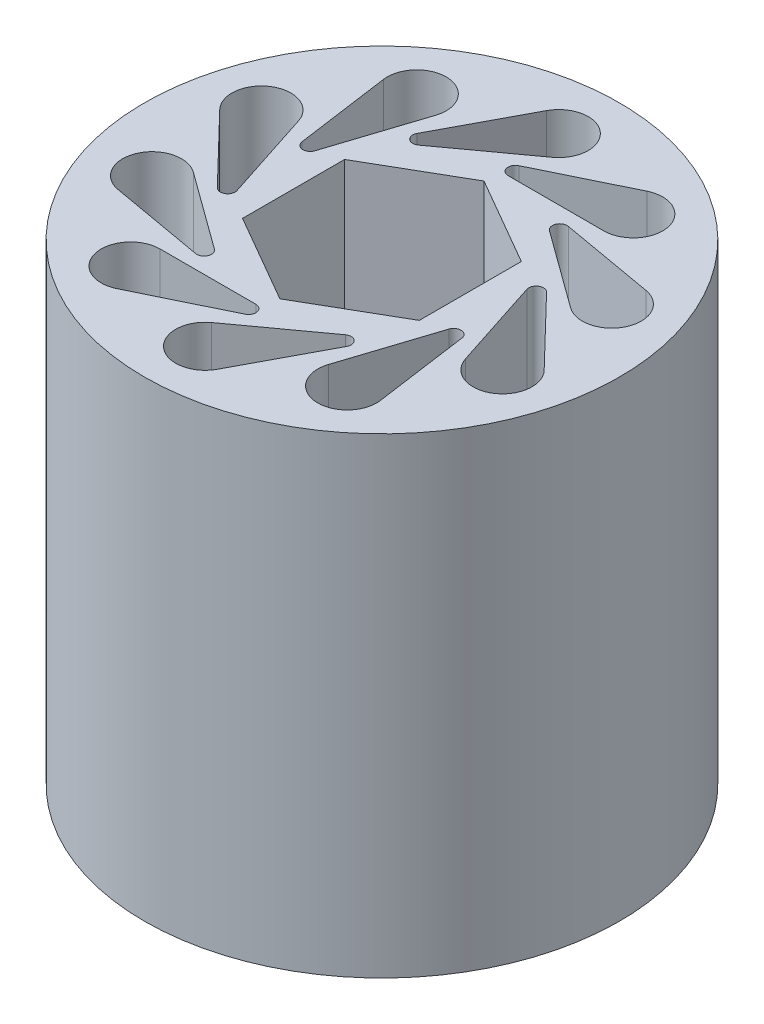
SolidWorks part; units mm, degrees
ref_plane "Front Plane" through (0, 0, 0) normal (0, 0, 1) x (1, 0, 0)
ref_plane "Top Plane" through (0, 0, 0) normal (0, 1, 0) x (1, 0, 0)
ref_plane "Right Plane" through (0, 0, 0) normal (1, 0, 0) x (0, 0, -1)
sketch "Sketch1" plane through (0, 0, 0) normal (0, 1, 0) x (1, 0, 0)
  line L0 (0, 0) -> (0, 25.6) construction
  line L1 (0, 12.8) -> (22.1703, 12.8) construction
  line L2 (0, 14.0898) -> (17.5057, 22.6239) construction
  line L3 (0.7937, 13.5938) -> (11.1125, 15.975) construction
  line L4 (0, 12.8) -> (19.7727, 12.8) construction
  line L5 (0.4459, 14.3072) -> (9.7212, 18.8289)
  line L6 (0.7937, 12.8) -> (11.1125, 12.8)
  line L7 (8.2915, 6.1775) -> (8.332, 6.1636)
  line L8 (8.7703, 11.3127) -> (18.932, 9.5189)
  line L9 (8.1658, 9.8889) -> (16.5139, 3.8237)
  line L10 (13.7448, 3.9971) -> (20.9114, -3.427)
  line L11 (12.4188, 3.2005) -> (15.6075, -6.6132)
  line L12 (13.4692, -4.8453) -> (14.9034, -15.0639)
  line L13 (11.9282, -4.7103) -> (8.7396, -14.524)
  line L14 (8.0488, -11.8369) -> (3.2027, -20.9469)
  line L15 (6.8815, -10.822) -> (-1.4666, -16.8872)
  line L16 (-0.4459, -14.3072) -> (-9.7212, -18.8289)
  line L17 (-0.7937, -12.8) -> (-11.1125, -12.8)
  line L18 (-8.7703, -11.3127) -> (-18.932, -9.5189)
  line L19 (-8.1658, -9.8889) -> (-16.5139, -3.8237)
  line L20 (0, 21.4691) -> (3.3271, 24.7962)
  line L21 (-12.8, 12.29) -> (-12.8, 22.6088) [skipped]
  line L22 (-20.4454, 24.5333) -> (-20.8126, 25.2866) [skipped]
  line L23 (-16.1802, 4.0758) -> (-25.9361, 7.4371) [skipped]
  line L24 (-15.3604, 5.3875) -> (-22.6568, 12.684) [skipped]
  line L25 (-11.9422, -2.811) -> (-21.2175, -7.3327) [skipped]
  line L26 (-12.29, -1.3037) -> (-22.6088, -1.3037) [skipped]
  line L27 (-11.0512, -9.5278) -> (-15.2391, -13.7157) [skipped]
  line L28 (-6.8663, -12.7832) -> (-8.9617, -18.865) [skipped]
  line L29 (1.3037, -13.3766) -> (1.3037, -14.1925) [skipped]
  line L30 (4.483, -3.8758) -> (7.6655, -10.4039) [skipped]
  line L31 (11.4871, -1.5143) -> (13.4593, -3.4864) [skipped]
  line L32 (-7.4205, 16.1802) -> (-4.0592, 25.9361) [skipped]
  line L33 (-13.7448, -3.9971) -> (-20.9114, 3.427)
  line L34 (-12.4188, -3.2005) -> (-15.6075, 6.6132)
  line L35 (-13.4692, 4.8453) -> (-14.9034, 15.0639)
  line L36 (-11.9282, 4.7103) -> (-8.7396, 14.524)
  line L37 (-8.0488, 11.8369) -> (-3.2027, 20.9469)
  line L38 (-6.8815, 10.822) -> (1.4666, 16.8872)
  line L40 (0, 10.9985) -> (-9.525, 5.4993)
  line L41 (-9.525, 5.4993) -> (-9.525, -5.4993)
  line L42 (-9.525, -5.4993) -> (0, -10.9985)
  line L43 (0, -10.9985) -> (9.525, -5.4993)
  line L44 (9.525, -5.4993) -> (9.525, 5.4993)
  line L45 (9.525, 5.4993) -> (0, 10.9985)
  circle A0 centre (0, 0) radius 25.6
  circle A1 centre (0, 0) radius 10.364 construction
  circle A2 centre (11.1125, 15.975) radius 3.175 construction
  circle A3 centre (0.7937, 13.5938) radius 0.7937 construction
  arc A4 (0.4459, 14.3072) -> (0.7937, 12.8) centre (0.7937, 13.5938) ccw
  arc A5 (11.1125, 12.8) -> (9.7212, 18.8289) centre (11.1125, 15.975) ccw
  arc A6 (1.5672, 13.7722) -> (1.5528, 13.8258) centre (0.7937, 13.5938) ccw
  arc A7 (16.5139, 3.8237) -> (18.932, 9.5189) centre (18.3801, 6.3923) ccw
  arc A8 (8.7703, 11.3127) -> (8.1658, 9.8889) centre (8.6324, 10.531) ccw
  arc A9 (15.6075, -6.6132) -> (20.9114, -3.427) centre (18.6271, -5.6321) ccw
  arc A10 (13.7448, 3.9971) -> (12.4188, 3.2005) centre (13.1737, 3.4458) ccw
  arc A11 (8.7396, -14.524) -> (14.9034, -15.0639) centre (11.7592, -15.5052) ccw
  arc A12 (13.4692, -4.8453) -> (11.9282, -4.7103) centre (12.6831, -4.9556) ccw
  arc A13 (-1.4666, -16.8872) -> (3.2027, -20.9469) centre (0.3997, -19.4558) ccw
  arc A14 (8.0488, -11.8369) -> (6.8815, -10.822) centre (7.348, -11.4641) ccw
  arc A15 (-11.1125, -12.8) -> (-9.7212, -18.8289) centre (-11.1125, -15.975) ccw
  arc A16 (-0.4459, -14.3072) -> (-0.7937, -12.8) centre (-0.7937, -13.5938) ccw
  arc A17 (-16.5139, -3.8237) -> (-18.932, -9.5189) centre (-18.3801, -6.3923) ccw
  arc A18 (-8.7703, -11.3127) -> (-8.1658, -9.8889) centre (-8.6324, -10.531) ccw
  arc A19 (-15.6075, 6.6132) -> (-20.9114, 3.427) centre (-18.6271, 5.6321) ccw
  arc A20 (-13.7448, -3.9971) -> (-12.4188, -3.2005) centre (-13.1737, -3.4458) ccw
  circle A21 centre (0, 0) radius 9.525 construction
  arc A22 (-14.3072, 11.9422) -> (-12.8, 12.29) centre (-13.5937, 12.29) ccw [skipped]
  arc A23 (-12.8, 22.6088) -> (-13.4499, 24.5335) centre (-15.975, 22.6088) ccw [skipped]
  arc A24 (-22.6568, 12.684) -> (-24.7783, 13.6115) centre (-24.9019, 10.4389) ccw [skipped]
  arc A25 (-16.1802, 4.0758) -> (-15.3604, 5.3875) centre (-15.9216, 4.8262) ccw [skipped]
  arc A26 (-22.6088, -1.3037) -> (-21.2175, -7.3327) centre (-22.6088, -4.4787) ccw [skipped]
  arc A27 (-11.9422, -2.811) -> (-12.29, -1.3037) centre (-12.29, -2.0975) ccw [skipped]
  arc A28 (-4.0758, -4.6839) -> (-5.3875, -3.8641) centre (-4.8262, -4.4254) ccw [skipped]
  arc A29 (-12.684, -11.1606) -> (-7.4371, -14.4399) centre (-10.4389, -13.4056) ccw [skipped]
  arc A30 (1.3037, -11.1125) -> (7.3327, -9.7212) centre (4.4787, -11.1125) ccw [skipped]
  arc A31 (2.811, -0.4459) -> (1.3037, -0.7937) centre (2.0975, -0.7937) ccw [skipped]
  arc A32 (4.6839, 7.4205) -> (3.8641, 6.1087) centre (4.4254, 6.67) ccw [skipped]
  arc A33 (11.1606, -1.1877) -> (14.4399, 4.0592) centre (13.4056, 1.0574) ccw [skipped]
  arc A34 (-7.4205, 16.1802) -> (-6.1087, 15.3604) centre (-6.67, 15.9216) ccw [skipped]
  arc A35 (-4.0493, 25.9643) -> (-4.1738, 25.5087) centre (-1.0574, 24.9019) ccw [skipped]
  arc A36 (-8.7396, 14.524) -> (-14.9034, 15.0639) centre (-11.7592, 15.5052) ccw
  arc A37 (-13.4692, 4.8453) -> (-11.9282, 4.7103) centre (-12.6831, 4.9556) ccw
  arc A38 (1.4666, 16.8872) -> (-3.2027, 20.9469) centre (-0.3997, 19.4558) ccw
  arc A39 (-8.0488, 11.8369) -> (-6.8815, 10.822) centre (-7.348, 11.4641) ccw
  point P65 (-5.7481, 5.7481)
  point P148 (0, 0)
  dimension "D1" = 11.1125
  dimension "D2" = 8
  dimension "D3" = 3.175
  dimension "D5" = 51.2
  dimension "D6" = 0.7937
  dimension "D4" = 10
extrude "Boss-Extrude1" add sketch "Sketch1" along normal blind 50.8
chamfer "Chamfer1" distance 0.2 angle 45 6 edges at (4.7625, 0, -8.2489) (9.525, 0, 0) (4.7625, 0, 8.2489) (-4.7625, 0, 8.2489) (-9.525, 0, 0) (-4.7625, 0, -8.2489)
